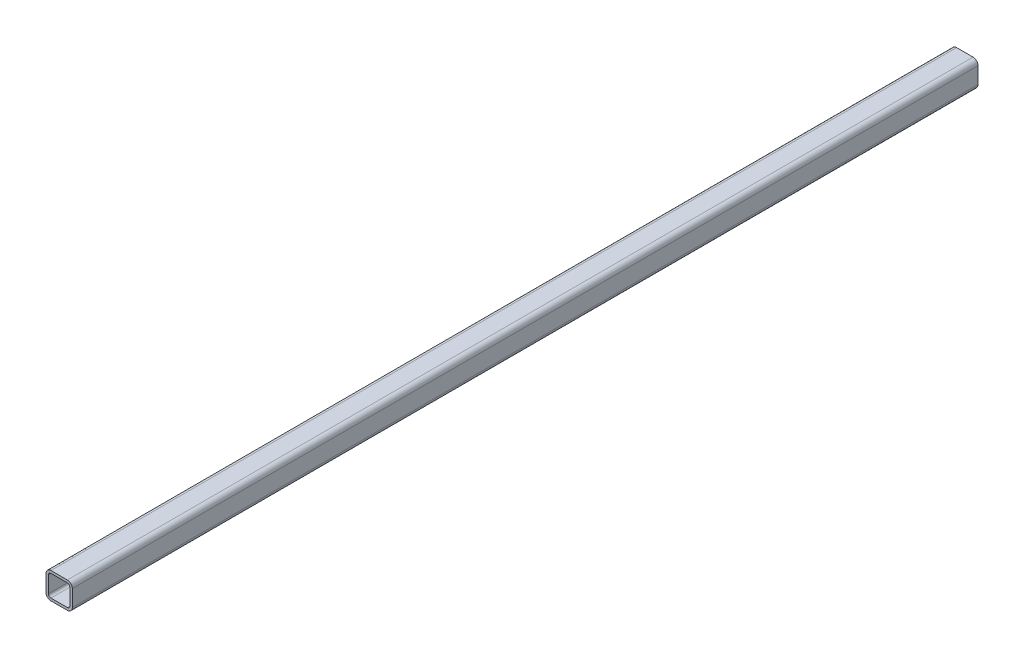
SolidWorks part; units mm, degrees
ref_plane "Płaszczyzna przednia" through (0, 0, 0) normal (0, 0, 1) x (1, 0, 0)
ref_plane "Płaszczyzna górna" through (0, 0, 0) normal (0, 1, 0) x (1, 0, 0)
ref_plane "Płaszczyzna prawa" through (0, 0, 0) normal (1, 0, 0) x (0, 0, -1)
sketch "Szkic1" plane through (0, 0, 0) normal (0, 0, 1) x (1, 0, 0)
  line L1 (9.53, 0) -> (41.27, 0)
  line L2 (0, 9.53) -> (0, 41.27)
  line L3 (9.53, 50.8) -> (41.27, 50.8)
  line L4 (50.8, 9.53) -> (50.8, 41.27)
  line L5 (9.52, 46.04) -> (41.28, 46.04)
  line L6 (4.76, 41.28) -> (4.76, 9.52)
  line L7 (9.52, 4.76) -> (41.28, 4.76)
  line L8 (46.04, 41.28) -> (46.04, 9.52)
  arc A0 (4.76, 9.52) -> (9.52, 4.76) centre (9.52, 9.52) ccw
  arc A1 (41.28, 4.76) -> (46.04, 9.52) centre (41.28, 9.52) ccw
  arc A2 (46.04, 41.28) -> (41.28, 46.04) centre (41.28, 41.28) ccw
  arc A3 (4.76, 41.28) -> (9.52, 46.04) centre (9.52, 41.28) cw
  arc A4 (41.27, 50.8) -> (50.8, 41.27) centre (41.27, 41.27) cw
  arc A5 (50.8, 9.53) -> (41.27, 0) centre (41.27, 9.53) cw
  arc A6 (9.53, 0) -> (0, 9.53) centre (9.53, 9.53) cw
  arc A7 (0, 41.27) -> (9.53, 50.8) centre (9.53, 41.27) cw
  point P23 (0, 0)
  dimension "D7" = 4.76
  dimension "D8" = 9.53
  dimension "D1" = 50.8
  dimension "D2" = 50.8
  dimension "D3" = 41.28
  dimension "D4" = 41.28
  dimension "D5" = 4.76
  dimension "D6" = 4.76
extrude "Dodanie-wyciągnięcie1" add sketch "Szkic1" along normal blind 1749.2
